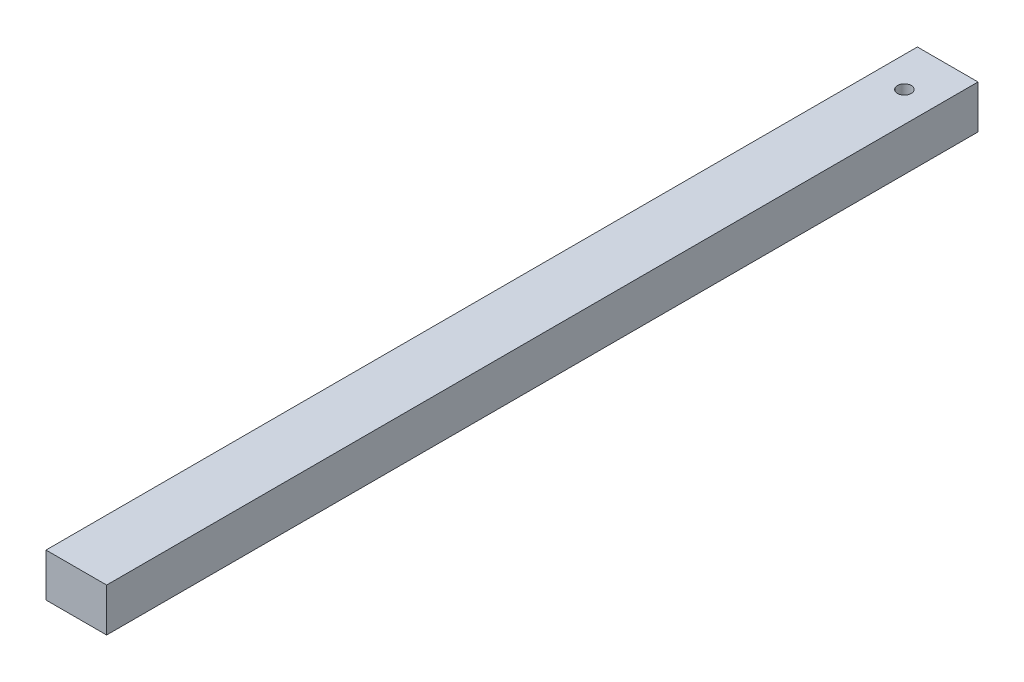
SolidWorks part; units mm, degrees
material "Beech"
ref_plane "Front Plane" through (0, 0, 0) normal (0, 0, 1) x (1, 0, 0)
ref_plane "Top Plane" through (0, 0, 0) normal (0, 1, 0) x (1, 0, 0)
ref_plane "Right Plane" through (0, 0, 0) normal (1, 0, 0) x (0, 0, -1)
sketch "Sketch2" plane through (0, 0, 0) normal (0, 0, 1) x (1, 0, 0)
  line L1 (-17.5, 12.5) -> (17.5, 12.5)
  line L2 (-17.5, 12.5) -> (-17.5, -12.5)
  line L3 (-17.5, -12.5) -> (17.5, -12.5)
  line L4 (17.5, 12.5) -> (17.5, -12.5)
  line L5 (-17.5, 12.5) -> (17.5, -12.5) construction
  line L6 (-17.5, -12.5) -> (17.5, 12.5) construction
  point P0 (0, 0)
  dimension "D1" = 35
  dimension "D2" = 25
extrude "Boss-Extrude1" add sketch "Sketch2" along normal blind 503
sketch "Sketch3" plane through (0, 12.5, 0) normal (0, 1, 0) x (1, 0, 0)
  line L0 (0, 0) -> (0, -25) construction
  circle A0 centre (0, -25) radius 4
  dimension "D2" = 8
  dimension "D1" = 25
extrude "Cut-Extrude2" cut sketch "Sketch3" against normal through all
